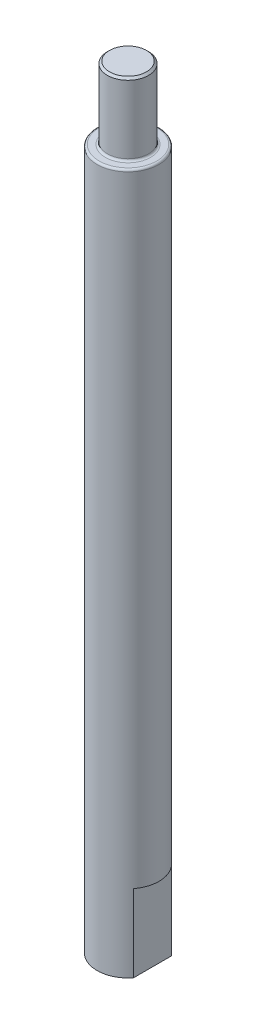
SolidWorks part; units mm, degrees
ref_plane "Front Plane" through (0, 0, 0) normal (0, 0, 1) x (1, 0, 0)
ref_plane "Top Plane" through (0, 0, 0) normal (0, 1, 0) x (1, 0, 0)
ref_plane "Right Plane" through (0, 0, 0) normal (1, 0, 0) x (0, 0, -1)
sketch "Sketch1" plane through (0, 0, 0) normal (0, 0, 1) x (1, 0, 0)
  line L0 (0, 0) -> (-6, 0)
  line L1 (-6, 0) -> (-6, 136)
  line L2 (-6, 136) -> (-4, 136)
  line L3 (-4, 136) -> (-4, 150)
  line L4 (-4, 150) -> (0, 150)
  line L5 (0, 150) -> (0, 0)
  point P3 (0, 0)
  dimension "D1" = 4
  dimension "D2" = 6
  dimension "D3" = 14
  dimension "D4" = 150
revolve "Revolve1" add sketch "Sketch1" angle 360 about L5
sketch "Sketch2" plane through (0, 0, 0) normal (0, 0, 1) x (1, 0, 0)
  line L0 (-6, 136) -> (-6, 0) construction
  line L1 (-7.25, 15) -> (-4.75, 15)
  line L2 (-7.25, 15) -> (-7.25, 0)
  line L3 (-7.25, 0) -> (-4.75, 0)
  line L4 (-4.75, 15) -> (-4.75, 0)
  line L5 (-7.25, 15) -> (-4.75, 0) construction
  line L6 (-7.25, 0) -> (-4.75, 15) construction
  line L7 (-6, 0) -> (6, 0) construction
  point P0 (-6, 7.5)
  dimension "D1" = 15
  dimension "D2" = 2.5
extrude "Cut-Extrude1" cut sketch "Sketch2" against normal mid plane 30
mirror "Mirror1" about plane through (0, 0, 0) normal (1, 0, 0) of "Cut-Extrude1"
chamfer "Chamfer1" distance 0.4 angle 45 1 edges at (-4, 150, 0)
fillet "Fillet1" radius 0.4 2 edges at (-6, 136, 0) (-4, 136, 0)
